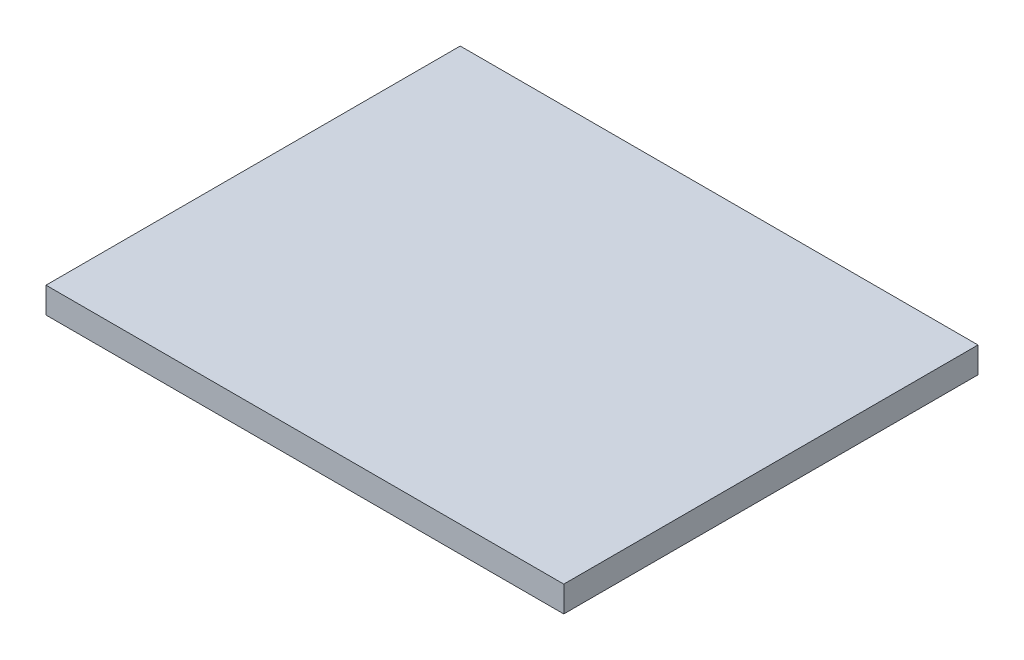
SolidWorks part; units mm, degrees
ref_plane "Front Plane" through (0, 0, 0) normal (0, 0, 1) x (1, 0, 0)
ref_plane "Top Plane" through (0, 0, 0) normal (0, 1, 0) x (1, 0, 0)
ref_plane "Right Plane" through (0, 0, 0) normal (1, 0, 0) x (0, 0, -1)
sketch "Sketch1" plane through (0, 0, 0) normal (0, 1, 0) x (1, 0, 0)
  line L1 (0, 0) -> (100, 0)
  line L2 (0, 0) -> (0, 80)
  line L3 (0, 80) -> (100, 80)
  line L4 (100, 0) -> (100, 80)
  dimension "D1" = 100
  dimension "D2" = 80
extrude "Boss-Extrude1" add sketch "Sketch1" along normal blind 5
